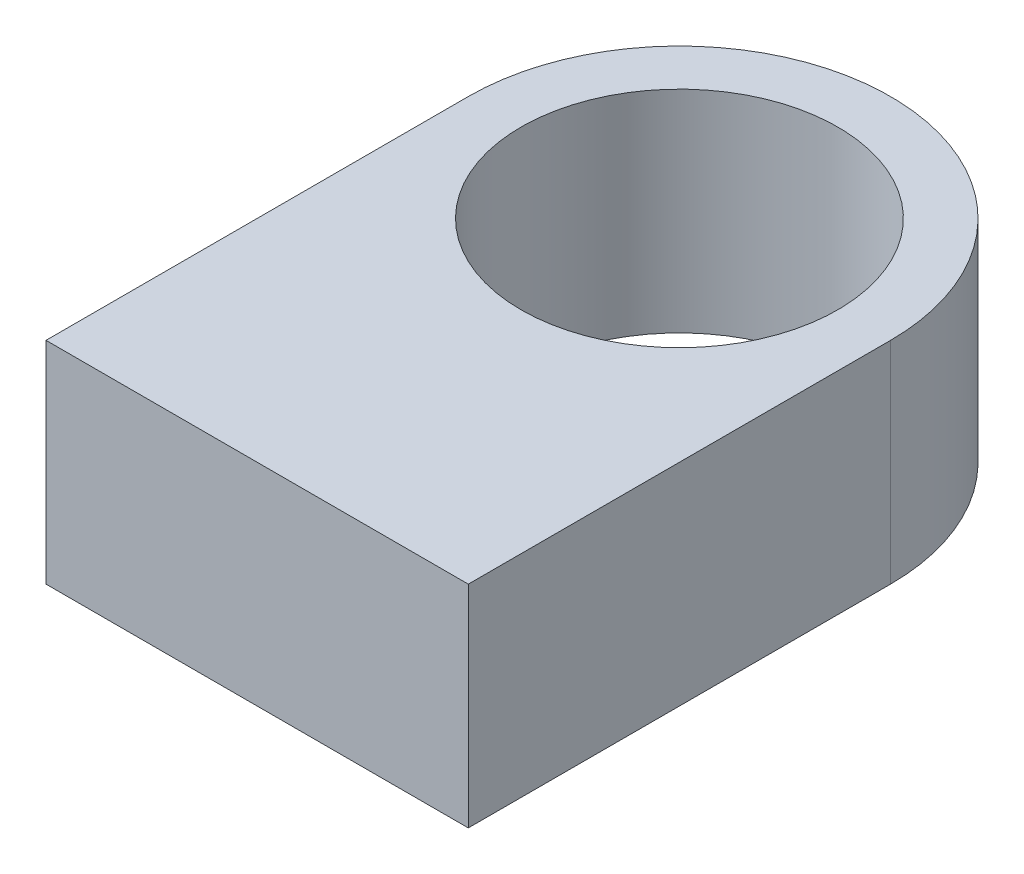
SolidWorks part; units mm, degrees
ref_plane "Plan de face" through (0, 0, 0) normal (0, 0, 1) x (1, 0, 0)
ref_plane "Plan de dessus" through (0, 0, 0) normal (0, 1, 0) x (1, 0, 0)
ref_plane "Plan de droite" through (0, 0, 0) normal (1, 0, 0) x (0, 0, -1)
sketch "Esquisse1" plane through (0, 0, 0) normal (0, 1, 0) x (1, 0, 0)
  line L0 (0, 0) -> (10, 0)
  line L1 (10, 0) -> (10, 20)
  line L2 (10, 20) -> (-10, 20)
  line L3 (-10, 20) -> (-10, 0)
  line L4 (-10, 0) -> (0, 0)
  line L5 (-10, 20) -> (-4.893, 20)
  circle A1 centre (0, 20) radius 7.5
  circle A2 centre (0, 20) radius 10
  dimension "D4" = 15
  dimension "D5" = 20
  dimension "D1" = 10
  dimension "D2" = 20
  dimension "D3" = 20
extrude "Boss.-Extru.1" add sketch "Esquisse1" along normal blind 10
